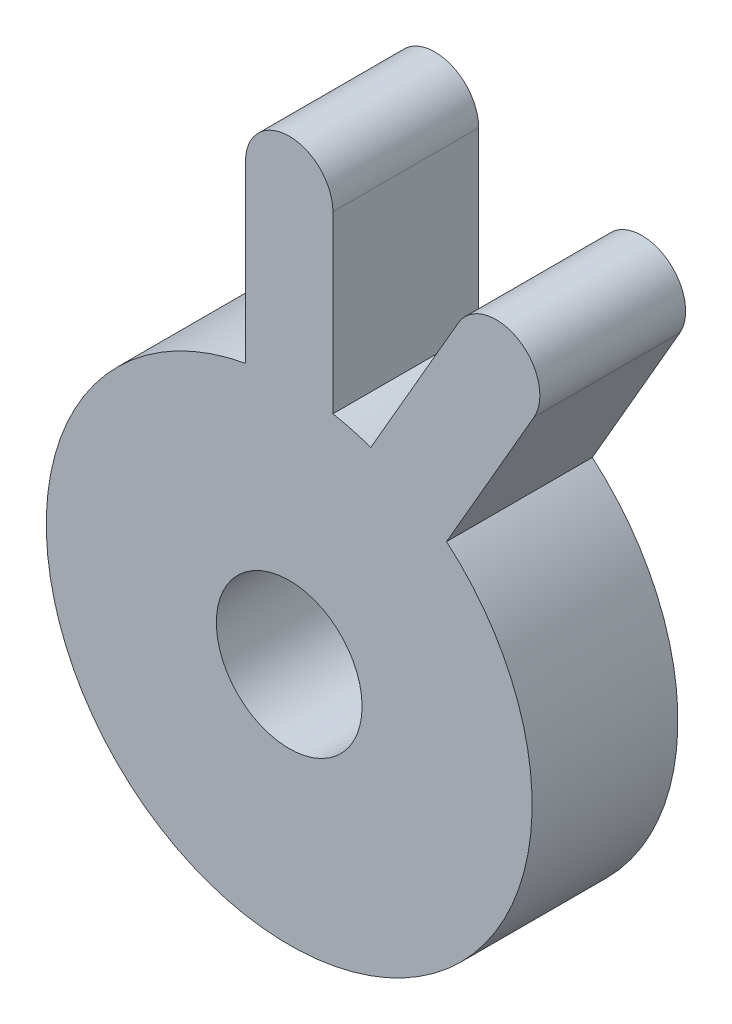
SolidWorks part; units mm, degrees
ref_plane "Front Plane" through (0, 0, 0) normal (0, 0, 1) x (1, 0, 0)
ref_plane "Top Plane" through (0, 0, 0) normal (0, 1, 0) x (1, 0, 0)
ref_plane "Right Plane" through (0, 0, 0) normal (1, 0, 0) x (0, 0, -1)
sketch "Sketch1" plane through (0, 0, 0) normal (0, 0, 1) x (1, 0, 0)
  line L0 (0, 0) -> (0, 51.188) construction
  line L1 (-4.5, 24.5917) -> (-4.5, 42.5917)
  line L2 (4.5, 24.5917) -> (4.5, 42.5917)
  line L3 (0, 0) -> (17.8221, 66.5129) construction
  line L4 (8.3987, 23.547) -> (17.3987, 39.1355)
  line L5 (16.1929, 19.047) -> (25.1929, 34.6355)
  line L6 (0, 0) -> (25.594, 44.3301) construction
  circle A0 centre (0, 0) radius 25
  circle A1 centre (0, 0) radius 7.5
  arc A2 (-4.5, 42.5917) -> (4.5, 42.5917) centre (0, 42.5917) cw
  arc A3 (25.1929, 34.6355) -> (17.3987, 39.1355) centre (21.2958, 36.8855) ccw
  circle A4 centre (0, 0) radius 34 construction
  dimension "D1" = 68
  dimension "D2" = 50
  dimension "D3" = 15
  dimension "D4" = 18
  dimension "D5" = 9
  dimension "D6" = 15
extrude "Boss-Extrude1" add sketch "Sketch1" along normal blind 15 contours A0 A1 | A2 L1 A0 L2 | L5 A3 L4 A0
